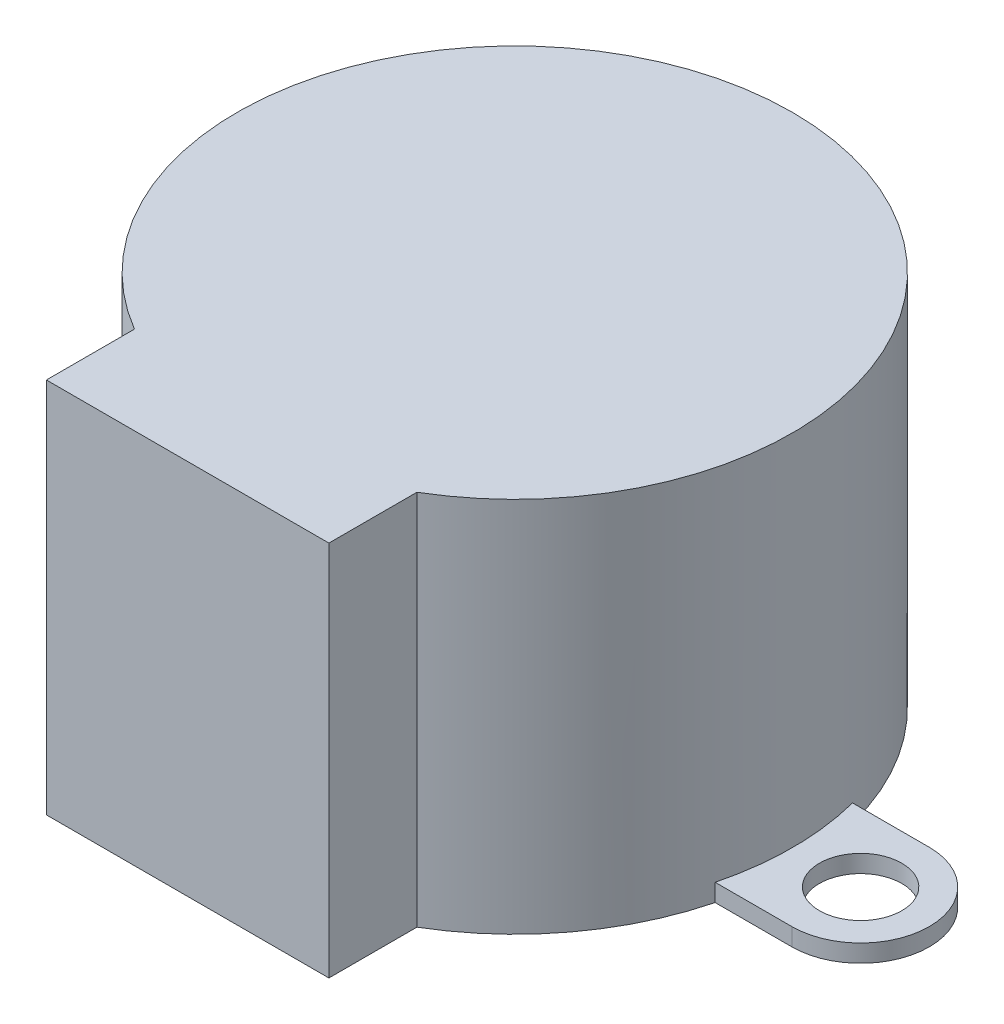
SolidWorks part; units mm, degrees
ref_plane "Front Plane" through (0, 0, 0) normal (0, 0, 1) x (1, 0, 0)
ref_plane "Top Plane" through (0, 0, 0) normal (0, 1, 0) x (1, 0, 0)
ref_plane "Right Plane" through (0, 0, 0) normal (1, 0, 0) x (0, 0, -1)
sketch "스케치1" plane through (0, 0, 0) normal (0, 1, 0) x (1, 0, 0)
  line L0 (0, -14.045) -> (0, 0) construction
  line L1 (-7.1437, -11.545) -> (7.1438, -11.545) construction
  line L2 (-7.1437, -11.545) -> (-7.1437, -16.545) construction
  line L3 (-7.1437, -16.545) -> (7.1438, -16.545)
  line L4 (7.1438, -11.545) -> (7.1438, -16.545) construction
  line L5 (-7.1437, -11.545) -> (7.1438, -16.545) construction
  line L6 (-7.1437, -16.545) -> (7.1438, -11.545) construction
  line L7 (7.1438, -12.0925) -> (7.1438, -16.545)
  line L8 (-7.1437, -12.0925) -> (-7.1437, -16.545)
  circle A0 centre (0, 0) radius 14.045 construction
  arc A1 (-7.1437, -12.0925) -> (7.1438, -12.0925) centre (0, 0) cw
  point P3 (0, -14.045)
  dimension "D1" = 28.09
  dimension "D2" = 14.2875
  dimension "D3" = 5
extrude "보스-돌출1" add sketch "스케치1" along normal blind 19.05
sketch "스케치2" plane through (0, 0, 0) normal (0, -1, 0) x (1, 0, 0)
  line L0 (0, 0) -> (0, 16.545) construction
  line L1 (-7.1437, 16.545) -> (7.1438, 16.545) construction
  line L2 (0, 0) -> (14.045, 0) construction
  line L5 (17.49, -3.475) -> (17.49, 3.475) construction
  line L10 (-17.49, 3.475) -> (-13.6083, 3.475)
  line L11 (17.49, 0) -> (-17.49, 0) construction
  line L12 (17.49, 0) -> (-17.49, 0) construction
  line L13 (17.49, 3.475) -> (13.6083, 3.475)
  line L14 (17.49, -3.475) -> (13.6083, -3.475)
  line L15 (-17.49, -3.475) -> (-13.6083, -3.475)
  arc A0 (-7.1437, 12.0925) -> (7.1438, 12.0925) centre (0, 0) ccw construction
  arc A1 (17.49, 3.475) -> (17.49, -3.475) centre (17.49, 0) cw
  circle A2 centre (17.49, 0) radius 2.0828
  circle A3 centre (-17.49, 0) radius 2.0828
  arc A4 (-17.49, 3.475) -> (-17.49, -3.475) centre (-17.49, 0) ccw
  arc A8 (-13.6083, 3.475) -> (-13.6083, -3.475) centre (0, 0) ccw
  arc A9 (13.6083, 3.475) -> (13.6083, -3.475) centre (0, 0) cw
  point P5 (15.4695, 0)
  point P16 (-20.965, 0)
  point P17 (20.965, 0)
  point P26 (-17.49, 0)
  point P27 (17.49, 0)
  dimension "D1" = 6.95
  dimension "D2" = 4.1656
  dimension "D7" = 34.98
  dimension "D4" = 3.445
extrude "보스-돌출2" add sketch "스케치2" against normal blind 0.889
sketch "스케치3" plane through (0, 0, 0) normal (0, -1, 0) x (1, 0, 0)
  line L0 (0, -8.03) -> (0, 0) construction
  circle A0 centre (0, -8.03) radius 4.635
  arc A2 (-13.6083, -3.475) -> (13.6083, -3.475) centre (0, 0) ccw construction
  point P2 (0, -12.665)
  point P4 (0, -14.045)
  dimension "D1" = 9.27
  dimension "D2" = 1.38
extrude "보스-돌출3" add sketch "스케치3" along normal blind 1.524
sketch "스케치4" plane through (0, -1.524, 0) normal (0, -1, 0) x (1, 0, 0)
  circle A0 centre (0, -8.03) radius 2.4892
  circle A1 centre (0, -8.03) radius 4.635 construction
  dimension "D1" = 4.9784
extrude "보스-돌출4" add sketch "스케치4" along normal blind 0.8001
sketch "스케치5" plane through (0, -2.3241, 0) normal (0, -1, 0) x (1, 0, 0)
  line L0 (2.0018, -9.5096) -> (-2.0018, -9.5096)
  line L1 (-2.4892, -9.5096) -> (2.4892, -9.5096) construction
  line L2 (-2.4892, -9.5096) -> (-2.4892, -6.5505) construction
  line L3 (-2.4892, -6.5505) -> (2.4892, -6.5505) construction
  line L4 (2.4892, -9.5096) -> (2.4892, -6.5505) construction
  line L5 (-2.4892, -9.5096) -> (2.4892, -6.5505) construction
  line L6 (-2.4892, -6.5505) -> (2.4892, -9.5096) construction
  line L7 (-2.0018, -6.5505) -> (2.0018, -6.5505)
  circle A0 centre (0, -8.03) radius 2.4892 construction
  circle A1 centre (0, -8.03) radius 2.4892 construction
  arc A2 (-2.0018, -6.5505) -> (-2.0018, -9.5096) centre (0, -8.03) ccw
  arc A3 (2.0018, -6.5505) -> (2.0018, -9.5096) centre (0, -8.03) cw
  point P0 (0, -8.03)
  point P8 (0, -10.5192)
  point P9 (-2.0018, -6.5505)
  point P12 (2.0018, -6.5505)
  point P13 (2.0018, -9.5096)
  point P14 (-2.0018, -9.5096)
  dimension "D2" = 2.9591
extrude "보스-돌출5" add sketch "스케치5" along normal blind 6.1976
